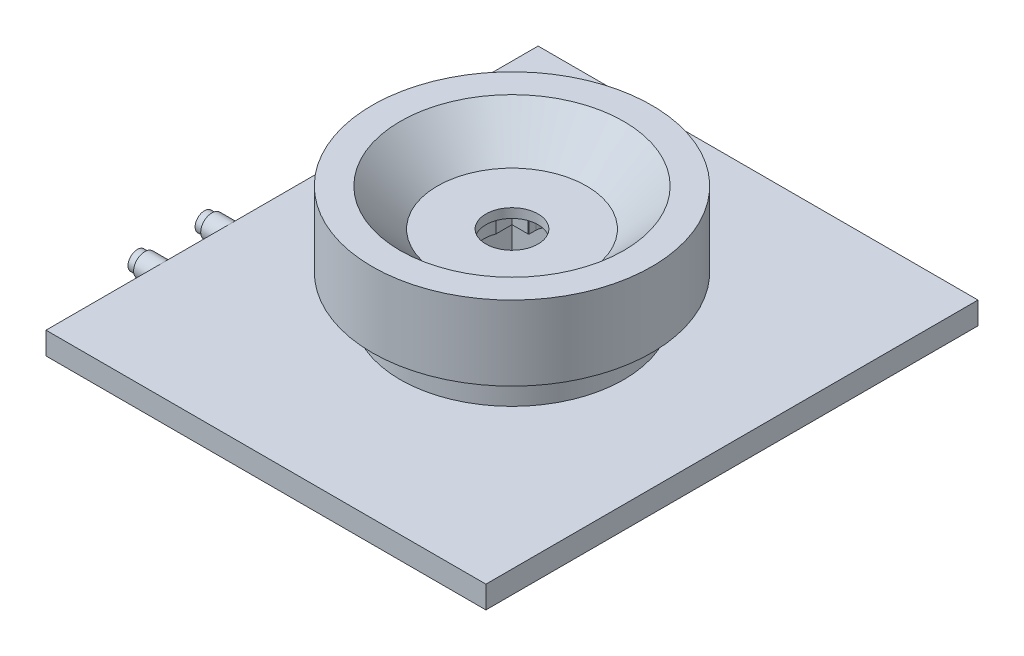
SolidWorks part; units mm, degrees
material "PE(聚乙烯)"
ref_plane "前视基准面" through (0, 0, 0) normal (0, 0, 1) x (1, 0, 0)
ref_plane "上视基准面" through (0, 0, 0) normal (0, 1, 0) x (1, 0, 0)
ref_plane "右视基准面" through (0, 0, 0) normal (1, 0, 0) x (0, 0, -1)
other "Configuration Table"
sketch "草图1" plane through (0, 0, 0) normal (0, 1, 0) x (1, 0, 0)
  line L1 (-59, 66) -> (59, 66)
  line L2 (-59, 66) -> (-59, -66)
  line L3 (-59, -66) -> (59, -66)
  line L4 (59, 66) -> (59, -66)
  line L5 (-59, 66) -> (59, -66) construction
  line L6 (-59, -66) -> (59, 66) construction
  point P0 (0, 0)
  dimension "D1" = 118
  dimension "D2" = 132
extrude "凸台-拉伸1" add sketch "草图1" along normal blind 6
sketch "草图2" plane through (0, 0, 0) normal (0, -1, 0) x (1, 0, 0)
  line L4 (-55, -62.5) -> (55, -62.5)
  line L5 (-55, 62.5) -> (-55, -62.5)
  line L6 (55, 62.5) -> (-55, 62.5)
  line L7 (55, -62.5) -> (55, 62.5)
  line L8 (-55, -62.5) -> (55, -62.5)
  line L9 (-55, 62.5) -> (-55, -62.5)
  line L10 (55, 62.5) -> (-55, 62.5)
  line L11 (55, -62.5) -> (55, 62.5)
  dimension "D1" = 0
extrude "切除-拉伸1" cut sketch "草图2" against normal blind 2
sketch "草图3" plane through (0, 6, 0) normal (0, 1, 0) x (1, 0, 0)
  circle A0 centre (0, 0) radius 30
  dimension "D1" = 60
extrude "凸台-拉伸2" add sketch "草图3" along normal blind 10
sketch "草图4" plane through (0, 16, 0) normal (0, 1, 0) x (1, 0, 0)
  circle A0 centre (0, 0) radius 37.5
  dimension "D1" = 75
extrude "凸台-拉伸3" add sketch "草图4" along normal blind 20
ref_plane "基准面1" through (0, 26, 0) normal (0, 1, 0) x (1, 0, 0)
sketch "草图6" plane through (0, 26, 0) normal (0, 1, 0) x (1, 0, 0)
  circle A0 centre (0, 0) radius 20
  dimension "D1" = 40
sketch "草图7" plane through (0, 36, 0) normal (0, 1, 0) x (1, 0, 0)
  circle A0 centre (0, 0) radius 30
  dimension "D1" = 60
loft "切除-放样2" cut profiles "草图6", "草图7"
sketch "草图8" plane through (0, 2, 0) normal (0, -1, 0) x (1, 0, 0)
  circle A0 centre (52.5, 60) radius 1.6 construction
  circle A1 centre (52.5, -60) radius 1.6 construction
  circle A2 centre (-52.5, -60) radius 1.6 construction
  circle A3 centre (-52.5, 60) radius 1.6 construction
  circle A4 centre (52.5, 60) radius 1.6
  circle A5 centre (52.5, -60) radius 1.6
  circle A6 centre (-52.5, -60) radius 1.6
  circle A7 centre (-52.5, 60) radius 1.6
extrude "切除-拉伸2" cut sketch "草图8" against normal blind 2.2
sketch "草图10" plane through (0, 2, 0) normal (0, -1, 0) x (1, 0, 0)
  line L4 (-16, -16) -> (16, -16)
  line L5 (16, -16) -> (16, 16)
  line L6 (16, 16) -> (-16, 16)
  line L7 (-16, 16) -> (-16, -16)
  line L8 (-16, -16) -> (16, -16) construction
  line L9 (16, -16) -> (16, 16) construction
  line L10 (16, 16) -> (-16, 16) construction
  line L11 (-16, 16) -> (-16, -16) construction
  line L20 (17, 17) -> (-17, 17)
  line L21 (-17, 17) -> (-17, -17)
  line L22 (-17, -17) -> (17, -17)
  line L23 (17, -17) -> (17, 17)
  dimension "D1" = 0
  dimension "D2" = 1
extrude "切除-拉伸3" cut sketch "草图10" against normal blind 18
sketch "草图11" plane through (0, 20, 0) normal (0, -1, 0) x (1, 0, 0)
  line L0 (-2.5936, -6.5) -> (-6.5, -6.5) construction
  line L1 (-6.5, -6.5) -> (-6.5, -2.5963) construction
  line L2 (2, -6.7064) -> (2, -9) construction
  line L3 (-2, -9) -> (-2, -6.7064) construction
  line L4 (6.5, -2.5963) -> (6.5, -6.5) construction
  line L5 (6.5, -6.5) -> (2.5936, -6.5) construction
  line L6 (-2, 6.71) -> (-2, 9.119) construction
  line L7 (2, 9.119) -> (2, 6.71) construction
  line L8 (2.6025, 6.5) -> (6.5, 6.5) construction
  line L9 (6.5, 6.5) -> (6.5, 2.5998) construction
  line L10 (-6.5, 2.5998) -> (-6.5, 6.5) construction
  line L11 (-6.5, 6.5) -> (-2.6025, 6.5) construction
  line L12 (-2.5936, -6.5) -> (-6.5, -6.5) construction
  line L13 (-6.5, -6.5) -> (-6.5, -2.5963) construction
  line L14 (2, -6.7064) -> (2, -9) construction
  line L15 (-2, -9) -> (-2, -6.7064) construction
  line L16 (6.5, -2.5963) -> (6.5, -6.5) construction
  line L17 (6.5, -6.5) -> (2.5936, -6.5) construction
  line L18 (-2, 6.71) -> (-2, 9.119) construction
  line L19 (2, 9.119) -> (2, 6.71) construction
  line L20 (2.6025, 6.5) -> (6.5, 6.5) construction
  line L21 (6.5, 6.5) -> (6.5, 2.5998) construction
  line L22 (-6.5, 2.5998) -> (-6.5, 6.5) construction
  line L23 (-6.5, 6.5) -> (-2.6025, 6.5) construction
  line L24 (-2.688, -7) -> (-7, -7)
  line L25 (-7, -7) -> (-7, -2.6908)
  line L26 (-7, 2.6944) -> (-7, 7)
  line L27 (-7, 7) -> (-2.6972, 7)
  line L28 (-2.5, 7.0728) -> (-2.5, 9.1331)
  line L29 (2.5, 9.1331) -> (2.5, 7.0728)
  line L30 (2.6972, 7) -> (7, 7)
  line L31 (7, 7) -> (7, 2.6944)
  line L32 (7, -2.6908) -> (7, -7)
  line L33 (7, -7) -> (2.688, -7)
  line L34 (2.5, -7.0693) -> (2.5, -9)
  line L35 (-2.5, -9) -> (-2.5, -7.0693)
  circle A0 centre (0, 0.0018) radius 7 construction
  arc A1 (-7, 2.6944) -> (-7, -2.6908) centre (0, 0.0018) ccw
  arc A2 (-2.5, 7.0728) -> (-2.6972, 7) centre (0, 0.0018) ccw
  arc A3 (-2, -9) -> (2, -9) centre (0, -9) ccw construction
  arc A4 (2.5, 9.1331) -> (-2.5, 9.1331) centre (0, 9) ccw
  arc A5 (2.6972, 7) -> (2.5, 7.0728) centre (0, 0.0018) ccw
  arc A6 (2, 9.119) -> (-2, 9.119) centre (0, 9) ccw construction
  arc A7 (7, -2.6908) -> (7, 2.6944) centre (0, 0.0018) ccw
  arc A8 (2.5, -7.0693) -> (2.688, -7) centre (0, 0.0018) ccw
  arc A9 (-6.5, 2.5998) -> (-6.5, -2.5963) centre (0, 0.0018) ccw construction
  arc A12 (-2, -9) -> (2, -9) centre (0, -9) ccw construction
  arc A15 (2, 9.119) -> (-2, 9.119) centre (0, 9) ccw construction
  arc A18 (-2.5936, -6.5) -> (-2, -6.7064) centre (0, 0.0018) ccw construction
  arc A19 (2, -6.7064) -> (2.5936, -6.5) centre (0, 0.0018) ccw construction
  arc A20 (6.5, -2.5963) -> (6.5, 2.5998) centre (0, 0.0018) ccw construction
  arc A21 (2.6025, 6.5) -> (2, 6.71) centre (0, 0.0018) ccw construction
  arc A22 (-2, 6.71) -> (-2.6025, 6.5) centre (0, 0.0018) ccw construction
  arc A23 (-2.5, -9) -> (2.5, -9) centre (0, -9) ccw
  arc A24 (-2.688, -7) -> (-2.5, -7.0693) centre (0, 0.0018) ccw
  dimension "D1" = 0.5
extrude "切除-拉伸4" cut sketch "草图11" against normal blind 3.5
sketch "草图12" plane through (0, 26, 0) normal (0, 1, 0) x (1, 0, 0)
  circle A0 centre (0, 0) radius 7
  dimension "D1" = 14
extrude "切除-拉伸5" cut sketch "草图12" against normal through all
sketch "草图13" plane through (0, 20, 0) normal (0, -1, 0) x (1, 0, 0)
  circle A0 centre (14, 14) radius 1.1 construction
  circle A1 centre (14, 14) radius 1.1 construction
  circle A2 centre (-14, -14) radius 1.1 construction
  circle A3 centre (-14, -14) radius 1.1 construction
  circle A4 centre (14, -14) radius 1.1 construction
  circle A5 centre (-14, 14) radius 1.1 construction
  circle A6 centre (14, -14) radius 1.1 construction
  circle A7 centre (-14, 14) radius 1.1 construction
  circle A8 centre (-14, 14) radius 1.35
  circle A9 centre (14, 14) radius 1.35
  circle A10 centre (14, -14) radius 1.35
  circle A11 centre (-14, -14) radius 1.35
  dimension "D1" = 2.7
extrude "切除-拉伸6" cut sketch "草图13" against normal blind 2
sketch "草图14" plane through (-59, 0, 0) normal (-1, 0, 0) x (0, 0, 1)
  line L0 (66, 6) -> (66, 0) construction
  circle A0 centre (34.5, 3) radius 3
  circle A1 centre (16.5, 3) radius 3
  dimension "D2" = 6
  dimension "D1" = 31.5
  dimension "D3" = 18
extrude "凸台-拉伸4" add sketch "草图14" along normal blind 5
sketch "草图15" plane through (-64, 0, 0) normal (-1, 0, 0) x (0, 0, 1)
  circle A6 centre (16.5, 3) radius 2.5
  circle A8 centre (34.5, 3) radius 2.5
  circle A9 centre (34.5, 3) radius 2.5
  dimension "D2" = 0.5
extrude "凸台-拉伸5" add sketch "草图15" along normal blind 2
sketch "草图16" plane through (-59, 0, 0) normal (-1, 0, 0) x (0, 0, 1)
  line L0 (-66, 3) -> (66, 3) construction
  line L1 (-66, 6) -> (-66, 0) construction
  line L2 (66, 6) -> (66, 0) construction
  circle A0 centre (-28.6648, 3) radius 2.5
  dimension "D1" = 5
extrude "切除-拉伸7" cut sketch "草图16" against normal blind 5
